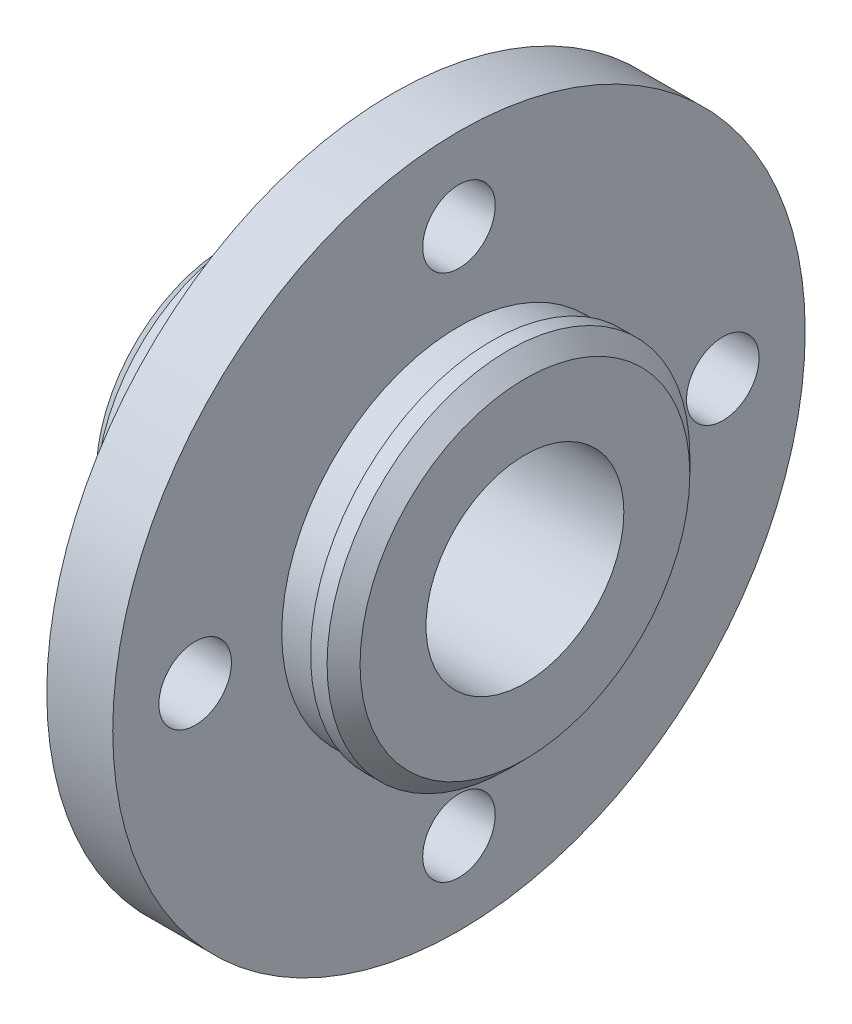
SolidWorks part; units mm, degrees
ref_plane "Спереди" through (0, 0, 0) normal (0, 0, 1) x (1, 0, 0)
ref_plane "Сверху" through (0, 0, 0) normal (0, 1, 0) x (1, 0, 0)
ref_plane "Справа" through (0, 0, 0) normal (1, 0, 0) x (0, 0, -1)
sketch "Эскиз1" plane through (0, 0, 0) normal (0, 0, 1) x (1, 0, 0)
  line L0 (0, 0) -> (-35.9286, 0) construction
  line L1 (0, -6) -> (0, -11)
  line L2 (0, -11) -> (-2, -11)
  line L3 (-2, -11) -> (-2, -10.75)
  line L4 (-2, -10.75) -> (-4, -10.75)
  line L5 (-4, -10.75) -> (-4, -21)
  line L6 (-4, -21) -> (-8, -21)
  line L7 (-8, -21) -> (-8, -9)
  line L8 (-8, -9) -> (-18, -9)
  line L9 (-18, -9) -> (-18, -6)
  line L10 (-18, -6) -> (0, -6)
  dimension "D1" = 12
  dimension "D2" = 22
  dimension "D3" = 21.5
  dimension "D4" = 4
  dimension "D5" = 2
  dimension "D6" = 42
  dimension "D7" = 10
  dimension "D8" = 18
  dimension "D9" = 18
revolve "Повернуть1" add sketch "Эскиз1" angle 360 about L0
sketch "Эскиз2" plane through (-4, 0, 0) normal (1, 0, 0) x (0, 0, -1)
  circle A0 centre (0, 16) radius 2.2
  dimension "D2" = 4.4
  dimension "D1" = 16
extrude "Вырез-Вытянуть1" cut sketch "Эскиз2" against normal through all
pattern_circular "Круговой массив1" count 4 over 360 about axis through (0, 0, 0) along (1, 0, 0) of "Вырез-Вытянуть1"
fillet "Скругление1" radius 1 1 edges at (-8, 0, -9)
chamfer "Фаска1" distance 1 angle 45 2 edges at (-18, 0, -9) (0, 0, -11)
